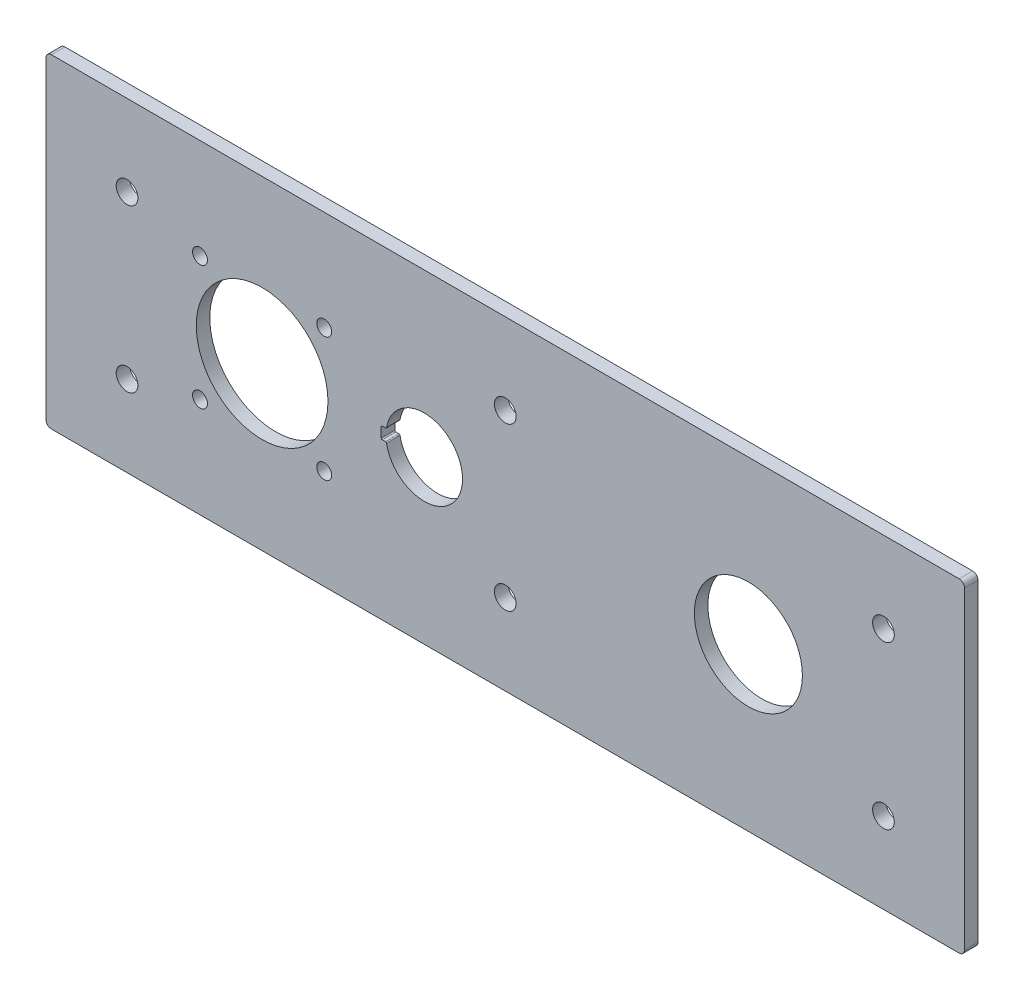
SolidWorks part; units mm, degrees
material "6061 Alloy"
ref_plane "Front Plane" through (0, 0, 0) normal (0, 0, 1) x (1, 0, 0)
ref_plane "Top Plane" through (0, 0, 0) normal (0, 1, 0) x (1, 0, 0)
ref_plane "Right Plane" through (0, 0, 0) normal (1, 0, 0) x (0, 0, -1)
sketch "Sketch1" plane through (0, 0, 0) normal (0, 0, 1) x (1, 0, 0)
  line L0 (107.95, 38.1) -> (107.95, -38.1) construction
  line L1 (1.27, 38.1) -> (214.63, 38.1)
  line L2 (0, 36.83) -> (0, -36.83)
  line L3 (1.27, -38.1) -> (214.63, -38.1)
  line L4 (215.9, 36.83) -> (215.9, -36.83)
  line L6 (0, 0) -> (215.9, 0) construction
  line L8 (88.9, 0) -> (215.9, 0) construction
  line L9 (79.7901, 1.397) -> (79.0575, 1.397)
  line L10 (79.7901, -1.397) -> (79.0575, -1.397)
  line L11 (78.8035, 1.143) -> (78.8035, -1.143)
  circle A0 centre (165.1, 0) radius 12.7
  circle A1 centre (50.8, 0) radius 15.4813
  circle A2 centre (36.195, 14.605) radius 1.7844 construction
  circle A3 centre (65.405, 14.605) radius 1.7844 construction
  circle A4 centre (65.405, -14.605) radius 1.7844 construction
  circle A5 centre (36.195, -14.605) radius 1.7843 construction
  circle A6 centre (19.05, 19.05) radius 2.5527
  circle A7 centre (196.85, 19.05) radius 2.5527
  circle A8 centre (196.85, -19.05) radius 2.5527
  circle A9 centre (19.05, -19.05) radius 2.5527
  arc A10 (1.27, 38.1) -> (0, 36.83) centre (1.27, 36.83) ccw
  arc A11 (80.04, -1.6057) -> (80.04, 1.6057) centre (88.9, 0) ccw
  arc A12 (214.63, 38.1) -> (215.9, 36.83) centre (214.63, 36.83) cw
  arc A13 (214.63, -38.1) -> (215.9, -36.83) centre (214.63, -36.83) ccw
  arc A14 (0, -36.83) -> (1.27, -38.1) centre (1.27, -36.83) ccw
  arc A15 (79.0575, 1.397) -> (78.8035, 1.143) centre (79.0575, 1.143) ccw
  arc A16 (79.7901, 1.397) -> (80.04, 1.6057) centre (79.7901, 1.651) ccw
  arc A17 (79.7901, -1.397) -> (80.04, -1.6057) centre (79.7901, -1.651) cw
  arc A18 (79.0575, -1.397) -> (78.8035, -1.143) centre (79.0575, -1.143) cw
  circle A19 centre (107.95, 19.05) radius 2.5527
  circle A20 centre (107.95, -19.05) radius 2.5527
  point P29 (0, 38.1)
  point P32 (215.9, 38.1)
  point P44 (0, -38.1)
  dimension "D3" = 9.0043
  dimension "D7" = 25.4
  dimension "D8" = 30.9626
  dimension "D9" = 3.5687
  dimension "D10" = 14.605
  dimension "D11" = 14.605
  dimension "D12" = 14.605
  dimension "D13" = 14.605
  dimension "D14" = 14.605
  dimension "D15" = 14.605
  dimension "D16" = 14.605
  dimension "D17" = 14.605
  dimension "D18" = 38.1
  dimension "D19" = 31.75
  dimension "D20" = 31.75
  dimension "D21" = 19.05
  dimension "D23" = 19.05
  dimension "D24" = 19.05
  dimension "D25" = 5.1054
  dimension "D26" = 1.27
  dimension "D27" = 0.254
  dimension "D1" = 76.2
  dimension "D2" = 215.9
  dimension "D4" = 10.0965
  dimension "D5" = 1.397
  dimension "D6" = 1.397
extrude "Extrude1" add sketch "Sketch1" against normal blind 3.175
hole_wizard "#6-32 Tapped Hole1" positions "Sketch3" profile "Sketch2" tap size "#6-32" standard "Ansi Inch" end condition through all
sketch "Sketch3" plane through (0, 0, 0) normal (0, 0, 1) x (1, 0, 0)
  point P0 (36.195, 14.605)
  point P1 (65.405, 14.605)
  point P3 (65.405, -14.605)
  point P5 (36.195, -14.605)
sketch "Sketch2" plane through (36.195, 14.605, 0) normal (1, 0, 0) x (0, -1, 0)
  line L0 (0, 0) -> (0, 3.175)
  line L1 (0, 3.175) -> (1.7526, 3.175)
  line L2 (1.7526, 3.175) -> (1.7526, 0)
  line L5 (1.7526, 0) -> (0, 0)
  line L11 (0, -6.35) -> (0, 107.95) construction
  dimension "Thread Major Dia." = 3.5052
  dimension "Thru Tap Drill Depth" = 3.175
